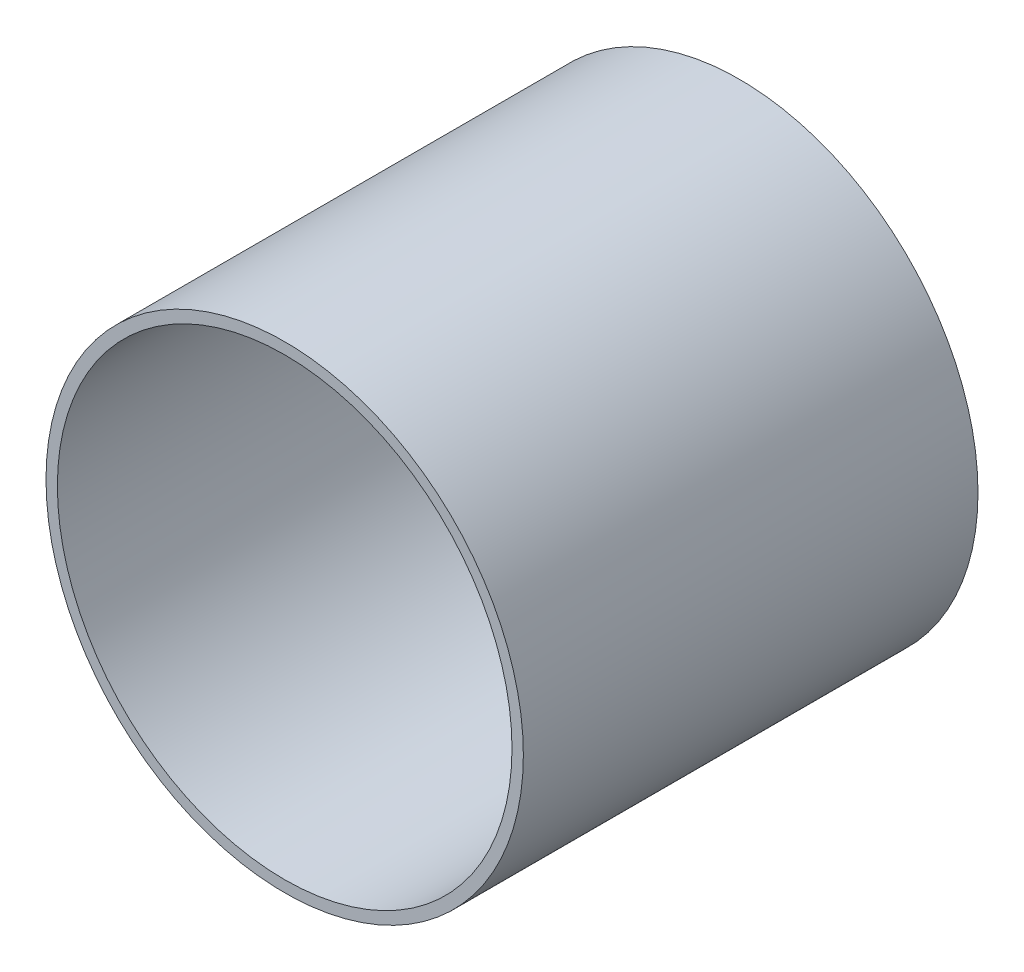
SolidWorks part; units mm, degrees
ref_plane "Ön Düzlem" through (0, 0, 0) normal (0, 0, 1) x (1, 0, 0)
ref_plane "Üst Düzlem" through (0, 0, 0) normal (0, 1, 0) x (1, 0, 0)
ref_plane "Sağ Düzlem" through (0, 0, 0) normal (1, 0, 0) x (0, 0, -1)
sketch "Çizim1" plane through (0, 0, 0) normal (0, 0, 1) x (1, 0, 0)
  circle A0 centre (0, 0) radius 20
  circle A1 centre (0, 0) radius 21
  dimension "D1" = 42
  dimension "D2" = 40
extrude "Yükseklik-Ekstrüzyon1" add sketch "Çizim1" along normal blind 40
